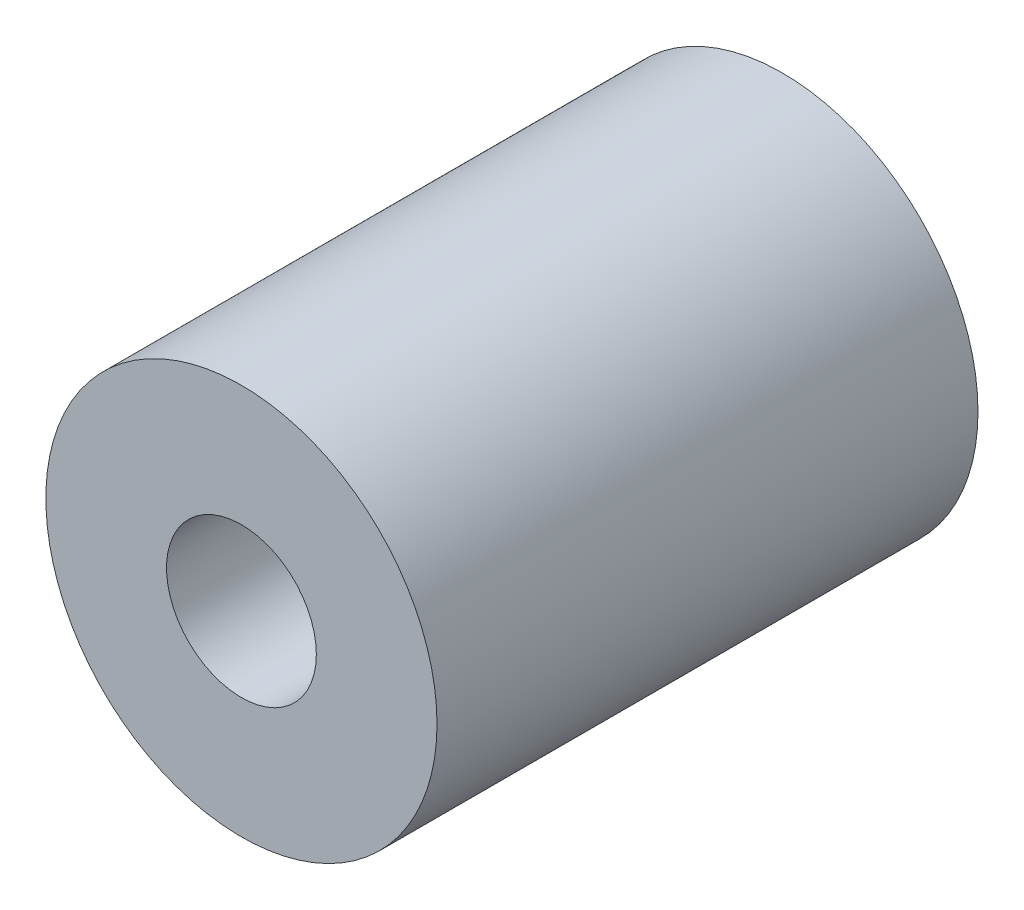
SolidWorks part; units mm, degrees
ref_plane "Front Plane" through (0, 0, 0) normal (0, 0, 1) x (1, 0, 0)
ref_plane "Top Plane" through (0, 0, 0) normal (0, 1, 0) x (1, 0, 0)
ref_plane "Right Plane" through (0, 0, 0) normal (1, 0, 0) x (0, 0, -1)
sketch "Sketch1" plane through (0, 0, 0) normal (0, 0, 1) x (1, 0, 0)
  circle A0 centre (0, 0) radius 18.7328
extrude "Boss-Extrude1" add sketch "Sketch1" along normal blind 26.416 and the other way blind 25.4
sketch "Sketch2" plane through (0, 0, 26.416) normal (0, 0, 1) x (1, 0, 0)
  circle A0 centre (0, 0) radius 7.175
extrude "Cut-Extrude1" cut sketch "Sketch2" against normal blind 192.024
